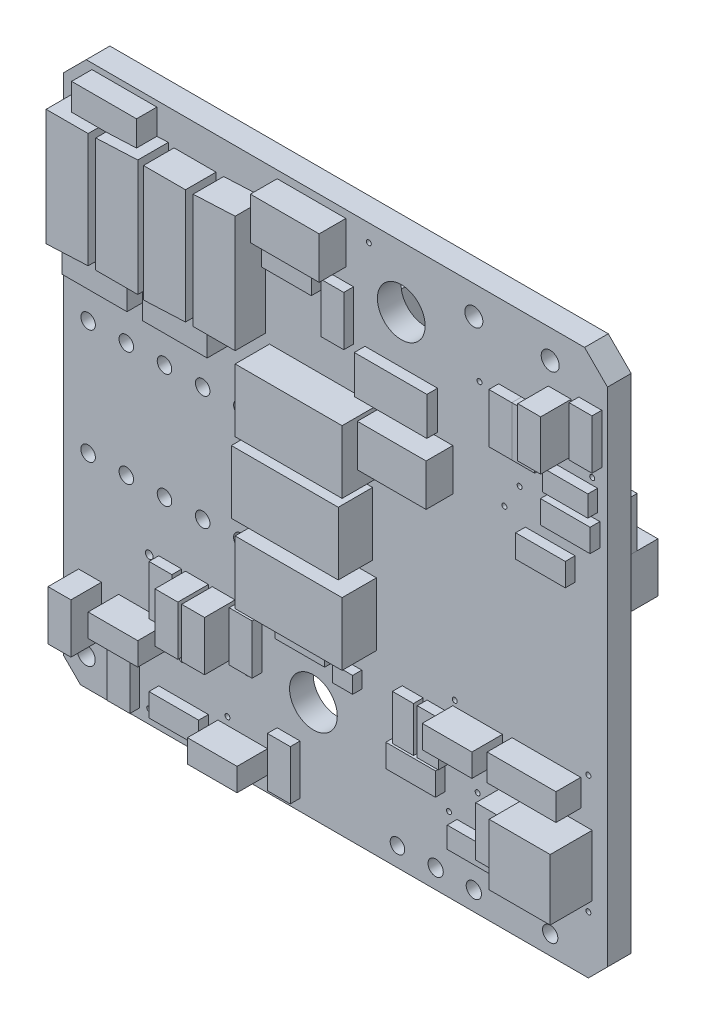
SolidWorks part; units mm, degrees
ref_plane "Front Plane" through (0, 0, 0) normal (0, 0, 1) x (1, 0, 0)
ref_plane "Top Plane" through (0, 0, 0) normal (0, 1, 0) x (1, 0, 0)
ref_plane "Right Plane" through (0, 0, 0) normal (1, 0, 0) x (0, 0, -1)
sketch "Sketch1" plane through (0, 0, 0) normal (0, 0, 1) x (1, 0, 0)
  line L0 (26.67, 71.501) -> (25.146, 69.977)
  line L1 (25.146, 69.977) -> (25.146, 36.449)
  line L2 (25.146, 36.449) -> (26.289, 35.306)
  line L3 (26.289, 35.306) -> (60.071, 35.306)
  line L4 (60.071, 35.306) -> (61.341, 36.576)
  line L5 (61.341, 36.576) -> (61.341, 69.977)
  line L6 (61.341, 69.977) -> (59.817, 71.501)
  line L7 (59.817, 71.501) -> (26.67, 71.501)
extrude "BOARD" add sketch "Sketch1" along normal blind 1.5748 separate body
sketch "Sketch2" plane through (0, 0, 0) normal (0, 0, 1) x (1, 0, 0)
  circle A0 centre (41.783, 42.037) radius 1.5875
  circle A1 centre (47.625, 67.437) radius 1.5875
extrude "NON-PLATED HOLES" cut sketch "Sketch2" along normal through all
sketch "Sketch3" plane through (0, 0, 0) normal (0, 0, 1) x (1, 0, 0)
  circle A0 centre (26.67, 69.723) radius 0.1651
  circle A1 centre (37.338, 41.529) radius 0.1651
  circle A2 centre (33.02, 40.132) radius 0.1651
  circle A3 centre (52.705, 44.323) radius 0.1651
  circle A4 centre (52.705, 42.291) radius 0.1651
  circle A5 centre (50.8, 40.259) radius 0.1651
  circle A6 centre (51.181, 46.863) radius 0.1651
  circle A7 centre (47.371, 57.531) radius 0.1651
  circle A8 centre (52.832, 66.04) radius 0.1651
  circle A9 centre (57.531, 36.576) radius 0.508
  circle A10 centre (60.071, 39.116) radius 0.1651
  circle A11 centre (60.071, 46.99) radius 0.1651
  circle A12 centre (54.483, 59.69) radius 0.1651
  circle A13 centre (60.325, 64.262) radius 0.1651
  circle A14 centre (26.67, 37.211) radius 0.6
  circle A15 centre (36.068, 38.354) radius 0.1651
  circle A16 centre (55.499, 61.341) radius 0.1651
  circle A17 centre (56.134, 38.1) radius 0.1651
  circle A18 centre (57.531, 69.596) radius 0.6
  circle A19 centre (30.861, 36.195) radius 0.1651
  circle A20 centre (52.451, 36.576) radius 0.508
  circle A21 centre (49.911, 36.576) radius 0.508
  circle A22 centre (47.371, 36.576) radius 0.4826
  circle A23 centre (38.1, 51.689) radius 0.1651
  circle A24 centre (45.466, 70.358) radius 0.1651
  circle A25 centre (30.861, 45.085) radius 0.254
  circle A26 centre (52.451, 69.596) radius 0.6
  circle A27 centre (26.797, 48.895) radius 0.4826
  circle A28 centre (31.877, 48.895) radius 0.4826
  circle A29 centre (34.417, 48.895) radius 0.4826
  circle A30 centre (26.797, 56.515) radius 0.4826
  circle A31 centre (31.877, 56.515) radius 0.4826
  circle A32 centre (34.417, 56.515) radius 0.4826
  circle A33 centre (29.337, 48.895) radius 0.4826
  circle A34 centre (36.957, 48.895) radius 0.4826
  circle A35 centre (29.337, 56.515) radius 0.4826
  circle A36 centre (36.957, 56.515) radius 0.4826
extrude "PLATED HOLES" cut sketch "Sketch3" along normal through all
ref_plane "Plane1" through (0, 0, 1.5748) normal (0, 0, 1) x (1, 0, 0)
sketch "Sketch4" plane through (0, 0, 1.5748) normal (0, 0, 1) x (1, 0, 0)
  line L0 (27.686, 38.608) -> (27.686, 41.91)
  line L1 (27.686, 41.91) -> (26.162, 41.91)
  line L2 (26.162, 41.91) -> (26.162, 38.608)
  line L3 (26.162, 38.608) -> (27.686, 38.608)
extrude "0805C-1" add sketch "Sketch4" along normal blind 2.032 separate body
sketch "Sketch5" plane through (0, 0, 1.5748) normal (0, 0, 1) x (1, 0, 0)
  line L0 (44.45, 64.008) -> (44.45, 67.31)
  line L1 (44.45, 67.31) -> (42.926, 67.31)
  line L2 (42.926, 67.31) -> (42.926, 64.008)
  line L3 (42.926, 64.008) -> (44.45, 64.008)
extrude "0805R-1" add sketch "Sketch5" along normal blind 0.6502 separate body
sketch "Sketch6" plane through (0, 0, 1.5748) normal (0, 0, 1) x (1, 0, 0)
  line L0 (42.291, 67.564) -> (38.989, 67.564)
  line L1 (38.989, 67.564) -> (38.989, 66.04)
  line L2 (38.989, 66.04) -> (42.291, 66.04)
  line L3 (42.291, 66.04) -> (42.291, 67.564)
extrude "0805R-2" add sketch "Sketch6" along normal blind 0.6502 separate body
sketch "Sketch7" plane through (0, 0, 0) normal (0, 0, 1) x (1, 0, 0)
  line L0 (47.752, 52.197) -> (51.054, 52.197)
  line L1 (51.054, 52.197) -> (51.054, 50.673)
  line L2 (51.054, 50.673) -> (47.752, 50.673)
  line L3 (47.752, 50.673) -> (47.752, 52.197)
extrude "0805C-2" add sketch "Sketch7" against normal blind 2.032 separate body
sketch "SOT23-5-1 [0]" plane through (0, 0, 0) normal (0, 0, 1) x (1, 0, 0)
  line L0 (50.8508, 48.9458) -> (50.8508, 47.5488)
  line L1 (50.8508, 47.5488) -> (47.9552, 47.5488)
  line L2 (47.9552, 47.5488) -> (47.9552, 48.9458)
  line L3 (47.9552, 48.9458) -> (50.8508, 48.9458)
sketch "Sketch9" plane through (0, 0, 0) normal (0, 0, 1) x (1, 0, 0)
  line L0 (50.2539, 62.3158) -> (50.2539, 63.6682)
  line L1 (50.2539, 63.6682) -> (51.3461, 63.6682)
  line L2 (51.3461, 63.6682) -> (51.3461, 62.3158)
  line L3 (51.3461, 62.3158) -> (50.2539, 62.3158)
extrude "SOD523-1" add sketch "Sketch9" against normal blind 0.6096 separate body
sketch "Sketch10" plane through (0, 0, 1.5748) normal (0, 0, 1) x (1, 0, 0)
  line L0 (60.325, 39.878) -> (60.325, 43.942)
  line L1 (60.325, 43.942) -> (56.261, 43.942)
  line L2 (56.261, 43.942) -> (56.261, 39.878)
  line L3 (56.261, 39.878) -> (60.325, 39.878)
extrude "L3838-1" add sketch "Sketch10" along normal blind 2.794 separate body
sketch "Sketch11" plane through (0, 0, 1.5748) normal (0, 0, 1) x (1, 0, 0)
  line L0 (55.88, 57.658) -> (59.182, 57.658)
  line L1 (59.182, 57.658) -> (59.182, 59.182)
  line L2 (59.182, 59.182) -> (55.88, 59.182)
  line L3 (55.88, 59.182) -> (55.88, 57.658)
extrude "0805R-3" add sketch "Sketch11" along normal blind 0.6502 separate body
sketch "Sketch12" plane through (0, 0, 0) normal (0, 0, 1) x (1, 0, 0)
  line L0 (56.007, 67.564) -> (59.309, 67.564)
  line L1 (59.309, 67.564) -> (59.309, 66.04)
  line L2 (59.309, 66.04) -> (56.007, 66.04)
  line L3 (56.007, 66.04) -> (56.007, 67.564)
extrude "0805C-3" add sketch "Sketch12" against normal blind 2.032 separate body
sketch "Sketch13" plane through (0, 0, 1.5748) normal (0, 0, 1) x (1, 0, 0)
  line L0 (57.682, 63.819) -> (57.682, 62.419)
  line L1 (57.682, 62.419) -> (60.682, 62.419)
  line L2 (60.682, 62.419) -> (60.682, 63.819)
  line L3 (60.682, 63.819) -> (57.682, 63.819)
extrude "RC0603-1" add sketch "Sketch13" along normal blind 0.6502 separate body
sketch "Sketch14" plane through (0, 0, 1.5748) normal (0, 0, 1) x (1, 0, 0)
  line L0 (55.626, 66.548) -> (55.626, 63.246)
  line L1 (55.626, 63.246) -> (57.15, 63.246)
  line L2 (57.15, 63.246) -> (57.15, 66.548)
  line L3 (57.15, 66.548) -> (55.626, 66.548)
extrude "0805R-4" add sketch "Sketch14" along normal blind 0.6502 separate body
sketch "Sketch15" plane through (0, 0, 1.5748) normal (0, 0, 1) x (1, 0, 0)
  line L0 (34.798, 37.846) -> (31.496, 37.846)
  line L1 (31.496, 37.846) -> (31.496, 36.322)
  line L2 (31.496, 36.322) -> (34.798, 36.322)
  line L3 (34.798, 36.322) -> (34.798, 37.846)
extrude "0805R-5" add sketch "Sketch15" along normal blind 0.6502 separate body
sketch "Sketch16" plane through (0, 0, 1.5748) normal (0, 0, 1) x (1, 0, 0)
  line L0 (34.798, 42.037) -> (34.798, 45.339)
  line L1 (34.798, 45.339) -> (33.274, 45.339)
  line L2 (33.274, 45.339) -> (33.274, 42.037)
  line L3 (33.274, 42.037) -> (34.798, 42.037)
extrude "0805C-4" add sketch "Sketch16" along normal blind 2.032 separate body
sketch "SOT23-1" plane through (0, 0, 1.5748) normal (0, 0, 1) x (1, 0, 0)
  line L0 (34.671, 39.243) -> (35.687, 39.243)
  line L1 (35.687, 39.243) -> (35.687, 40.767)
  line L2 (35.687, 40.767) -> (35.687, 39.243)
  line L3 (35.687, 39.243) -> (34.671, 39.243)
sketch "Sketch18" plane through (0, 0, 1.5748) normal (0, 0, 1) x (1, 0, 0)
  line L0 (33.02, 42.037) -> (33.02, 45.339)
  line L1 (33.02, 45.339) -> (31.496, 45.339)
  line L2 (31.496, 45.339) -> (31.496, 42.037)
  line L3 (31.496, 42.037) -> (33.02, 42.037)
extrude "0805R-6" add sketch "Sketch18" along normal blind 0.6502 separate body
sketch "Sketch19" plane through (0, 0, 1.5748) normal (0, 0, 1) x (1, 0, 0)
  line L0 (36.576, 42.037) -> (36.576, 45.339)
  line L1 (36.576, 45.339) -> (35.052, 45.339)
  line L2 (35.052, 45.339) -> (35.052, 42.037)
  line L3 (35.052, 42.037) -> (36.576, 42.037)
extrude "0805C-5" add sketch "Sketch19" along normal blind 2.032 separate body
sketch "Sketch20" plane through (0, 0, 1.5748) normal (0, 0, 1) x (1, 0, 0)
  line L0 (39.37, 39.37) -> (39.37, 36.068)
  line L1 (39.37, 36.068) -> (40.894, 36.068)
  line L2 (40.894, 36.068) -> (40.894, 39.37)
  line L3 (40.894, 39.37) -> (39.37, 39.37)
extrude "0805R-7" add sketch "Sketch20" along normal blind 0.6502 separate body
sketch "Sketch21" plane through (0, 0, 1.5748) normal (0, 0, 1) x (1, 0, 0)
  line L0 (39.878, 45.085) -> (43.18, 45.085)
  line L1 (43.18, 45.085) -> (43.18, 46.609)
  line L2 (43.18, 46.609) -> (39.878, 46.609)
  line L3 (39.878, 46.609) -> (39.878, 45.085)
extrude "0805R-8" add sketch "Sketch21" along normal blind 0.6502 separate body
sketch "Sketch22" plane through (0, 0, 0) normal (0, 0, 1) x (1, 0, 0)
  line L0 (49.784, 58.674) -> (49.784, 61.976)
  line L1 (49.784, 61.976) -> (51.308, 61.976)
  line L2 (51.308, 61.976) -> (51.308, 58.674)
  line L3 (51.308, 58.674) -> (49.784, 58.674)
extrude "0805C-6" add sketch "Sketch22" against normal blind 2.032 separate body
sketch "Sketch23" plane through (0, 0, 1.5748) normal (0, 0, 1) x (1, 0, 0)
  line L0 (49.338, 42.95) -> (50.738, 42.95)
  line L1 (50.738, 42.95) -> (50.738, 45.95)
  line L2 (50.738, 45.95) -> (49.338, 45.95)
  line L3 (49.338, 45.95) -> (49.338, 42.95)
extrude "RC0603-2" add sketch "Sketch23" along normal blind 0.6502 separate body
sketch "Sketch24" plane through (0, 0, 1.5748) normal (0, 0, 1) x (1, 0, 0)
  line L0 (47.687, 42.95) -> (49.087, 42.95)
  line L1 (49.087, 42.95) -> (49.087, 45.95)
  line L2 (49.087, 45.95) -> (47.687, 45.95)
  line L3 (47.687, 45.95) -> (47.687, 42.95)
extrude "RC0603-3" add sketch "Sketch24" along normal blind 0.6502 separate body
sketch "Sketch25" plane through (0, 0, 0) normal (0, 0, 1) x (1, 0, 0)
  line L0 (47.879, 46.101) -> (51.181, 46.101)
  line L1 (51.181, 46.101) -> (51.181, 44.577)
  line L2 (51.181, 44.577) -> (47.879, 44.577)
  line L3 (47.879, 44.577) -> (47.879, 46.101)
extrude "0805C-7" add sketch "Sketch25" against normal blind 2.032 separate body
sketch "Sketch26" plane through (0, 0, 0) normal (0, 0, 1) x (1, 0, 0)
  line L0 (49.911, 54.356) -> (49.911, 57.658)
  line L1 (49.911, 57.658) -> (51.435, 57.658)
  line L2 (51.435, 57.658) -> (51.435, 54.356)
  line L3 (51.435, 54.356) -> (49.911, 54.356)
extrude "0805C-8" add sketch "Sketch26" against normal blind 2.032 separate body
sketch "Sketch27" plane through (0, 0, 1.5748) normal (0, 0, 1) x (1, 0, 0)
  line L0 (51.054, 58.674) -> (51.054, 61.468)
  line L1 (51.054, 61.468) -> (46.482, 61.468)
  line L2 (46.482, 61.468) -> (46.482, 58.674)
  line L3 (46.482, 58.674) -> (51.054, 58.674)
extrude "1210HV-1" add sketch "Sketch27" along normal blind 1.778 separate body
sketch "Sketch28" plane through (0, 0, 0) normal (0, 0, 1) x (1, 0, 0)
  line L0 (49.911, 57.658) -> (49.911, 54.356)
  line L1 (49.911, 54.356) -> (48.387, 54.356)
  line L2 (48.387, 54.356) -> (48.387, 57.658)
  line L3 (48.387, 57.658) -> (49.911, 57.658)
extrude "0805R-9" add sketch "Sketch28" against normal blind 0.6502 separate body
sketch "Sketch29" plane through (0, 0, 1.5748) normal (0, 0, 1) x (1, 0, 0)
  line L0 (54.61, 43.688) -> (54.61, 40.386)
  line L1 (54.61, 40.386) -> (56.134, 40.386)
  line L2 (56.134, 40.386) -> (56.134, 43.688)
  line L3 (56.134, 43.688) -> (54.61, 43.688)
extrude "0805C-9" add sketch "Sketch29" along normal blind 2.032 separate body
sketch "Sketch30" plane through (0, 0, 1.5748) normal (0, 0, 1) x (1, 0, 0)
  line L0 (59.563, 44.831) -> (59.563, 46.609)
  line L1 (59.563, 46.609) -> (54.991, 46.609)
  line L2 (54.991, 46.609) -> (54.991, 44.831)
  line L3 (54.991, 44.831) -> (59.563, 44.831)
extrude "DIODE_SMF-1" add sketch "Sketch30" along normal blind 1.651 separate body
sketch "Sketch31" plane through (0, 0, 1.5748) normal (0, 0, 1) x (1, 0, 0)
  line L0 (26.035, 61.595) -> (28.829, 61.722)
  line L1 (28.829, 61.722) -> (28.829, 69.342)
  line L2 (28.829, 69.342) -> (26.035, 69.342)
  line L3 (26.035, 69.342) -> (26.035, 61.722)
  line L4 (26.035, 61.722) -> (26.035, 61.595)
extrude "MICROSEMI_A-1" add sketch "Sketch31" along normal blind 2.032 separate body
sketch "Sketch32" plane through (0, 0, 1.5748) normal (0, 0, 1) x (1, 0, 0)
  line L0 (32.512, 61.595) -> (35.306, 61.722)
  line L1 (35.306, 61.722) -> (35.306, 69.342)
  line L2 (35.306, 69.342) -> (32.512, 69.342)
  line L3 (32.512, 69.342) -> (32.512, 61.722)
  line L4 (32.512, 61.722) -> (32.512, 61.595)
extrude "MICROSEMI_A-2" add sketch "Sketch32" along normal blind 2.032 separate body
sketch "Sketch33" plane through (0, 0, 1.5748) normal (0, 0, 1) x (1, 0, 0)
  line L0 (57.404, 68.072) -> (57.404, 64.77)
  line L1 (57.404, 64.77) -> (58.928, 64.77)
  line L2 (58.928, 64.77) -> (58.928, 68.072)
  line L3 (58.928, 68.072) -> (57.404, 68.072)
extrude "0805C-10" add sketch "Sketch33" along normal blind 2.032 separate body
sketch "Sketch34" plane through (0, 0, 1.5748) normal (0, 0, 1) x (1, 0, 0)
  line L0 (32.131, 41.783) -> (28.829, 41.783)
  line L1 (28.829, 41.783) -> (28.829, 40.259)
  line L2 (28.829, 40.259) -> (32.131, 40.259)
  line L3 (32.131, 40.259) -> (32.131, 41.783)
extrude "0805C-11" add sketch "Sketch34" along normal blind 2.032 separate body
sketch "Sketch35" plane through (0, 0, 1.5748) normal (0, 0, 1) x (1, 0, 0)
  line L0 (27.051, 71.12) -> (27.051, 69.342)
  line L1 (27.051, 69.342) -> (31.369, 69.342)
  line L2 (31.369, 69.342) -> (31.369, 71.12)
  line L3 (31.369, 71.12) -> (27.051, 71.12)
extrude "1206C-1" add sketch "Sketch35" along normal blind 1.3513 separate body
sketch "CONN3_100-1 [0]" plane through (0, 0, 1.5748) normal (0, 0, 1) x (1, 0, 0)
  line L0 (46.101, 37.846) -> (46.101, 35.306)
  line L1 (46.101, 35.306) -> (53.721, 35.306)
  line L2 (53.721, 35.306) -> (53.721, 37.846)
  line L3 (53.721, 37.846) -> (46.101, 37.846)
sketch "Sketch37" plane through (0, 0, 1.5748) normal (0, 0, 1) x (1, 0, 0)
  line L0 (38.354, 42.037) -> (38.354, 45.339)
  line L1 (38.354, 45.339) -> (36.83, 45.339)
  line L2 (36.83, 45.339) -> (36.83, 42.037)
  line L3 (36.83, 42.037) -> (38.354, 42.037)
extrude "0805R-10" add sketch "Sketch37" along normal blind 0.6502 separate body
sketch "Sketch38" plane through (0, 0, 1.5748) normal (0, 0, 1) x (1, 0, 0)
  line L0 (50.546, 42.799) -> (47.244, 42.799)
  line L1 (47.244, 42.799) -> (47.244, 41.275)
  line L2 (47.244, 41.275) -> (50.546, 41.275)
  line L3 (50.546, 41.275) -> (50.546, 42.799)
extrude "0805R-11" add sketch "Sketch38" along normal blind 0.6502 separate body
sketch "Sketch39" plane through (0, 0, 1.5748) normal (0, 0, 1) x (1, 0, 0)
  line L0 (51.332, 40.07) -> (51.332, 38.67)
  line L1 (51.332, 38.67) -> (54.332, 38.67)
  line L2 (54.332, 38.67) -> (54.332, 40.07)
  line L3 (54.332, 40.07) -> (51.332, 40.07)
extrude "RC0603-4" add sketch "Sketch39" along normal blind 0.6502 separate body
sketch "SOT23-5-2 [0]" plane through (0, 0, 1.5748) normal (0, 0, 1) x (1, 0, 0)
  line L0 (54.1528, 41.3512) -> (54.1528, 42.7482)
  line L1 (54.1528, 42.7482) -> (51.2572, 42.7482)
  line L2 (51.2572, 42.7482) -> (51.2572, 41.3512)
  line L3 (51.2572, 41.3512) -> (54.1528, 41.3512)
sketch "Sketch41" plane through (0, 0, 1.5748) normal (0, 0, 1) x (1, 0, 0)
  line L0 (45.974, 47.117) -> (45.974, 51.308)
  line L1 (45.974, 51.308) -> (38.862, 51.308)
  line L2 (38.862, 51.308) -> (38.862, 47.117)
  line L3 (38.862, 47.117) -> (45.974, 47.117)
extrude "DIODESMB-1" add sketch "Sketch41" along normal blind 2.286 separate body
sketch "Sketch42" plane through (0, 0, 0) normal (0, 0, 1) x (1, 0, 0)
  line L0 (59.563, 56.007) -> (59.563, 59.309)
  line L1 (59.563, 59.309) -> (61.087, 59.309)
  line L2 (61.087, 59.309) -> (61.087, 56.007)
  line L3 (61.087, 56.007) -> (59.563, 56.007)
extrude "0805C-12" add sketch "Sketch42" against normal blind 2.032 separate body
sketch "Sketch43" plane through (0, 0, 1.5748) normal (0, 0, 1) x (1, 0, 0)
  line L0 (54.102, 66.548) -> (54.102, 63.246)
  line L1 (54.102, 63.246) -> (55.626, 63.246)
  line L2 (55.626, 63.246) -> (55.626, 66.548)
  line L3 (55.626, 66.548) -> (54.102, 66.548)
extrude "0805R-12" add sketch "Sketch43" along normal blind 0.6502 separate body
sketch "Sketch44" plane through (0, 0, 1.5748) normal (0, 0, 1) x (1, 0, 0)
  line L0 (50.038, 61.722) -> (50.038, 64.262)
  line L1 (50.038, 64.262) -> (45.212, 64.262)
  line L2 (45.212, 64.262) -> (45.212, 61.722)
  line L3 (45.212, 61.722) -> (50.038, 61.722)
extrude "1206RHV-1" add sketch "Sketch44" along normal blind 0.7112 separate body
sketch "Sketch45" plane through (0, 0, 1.5748) normal (0, 0, 1) x (1, 0, 0)
  line L0 (26.416, 61.468) -> (26.416, 59.69)
  line L1 (26.416, 59.69) -> (30.734, 59.69)
  line L2 (30.734, 59.69) -> (30.734, 61.468)
  line L3 (30.734, 61.468) -> (26.416, 61.468)
extrude "1206C-2" add sketch "Sketch45" along normal blind 1.3513 separate body
sketch "SOT23-2" plane through (0, 0, 1.5748) normal (0, 0, 1) x (1, 0, 0)
  line L0 (30.353, 44.323) -> (30.353, 45.339)
  line L1 (30.353, 45.339) -> (28.829, 45.339)
  line L2 (28.829, 45.339) -> (30.353, 45.339)
  line L3 (30.353, 45.339) -> (30.353, 44.323)
sketch "Sketch47" plane through (0, 0, 1.5748) normal (0, 0, 1) x (1, 0, 0)
  line L0 (28.702, 39.243) -> (28.702, 35.941)
  line L1 (28.702, 35.941) -> (30.226, 35.941)
  line L2 (30.226, 35.941) -> (30.226, 39.243)
  line L3 (30.226, 39.243) -> (28.702, 39.243)
extrude "0805R-13" add sketch "Sketch47" along normal blind 0.6502 separate body
sketch "Sketch48" plane through (0, 0, 0) normal (0, 0, 1) x (1, 0, 0)
  line L0 (61.087, 62.611) -> (61.087, 59.309)
  line L1 (61.087, 59.309) -> (59.563, 59.309)
  line L2 (59.563, 59.309) -> (59.563, 62.611)
  line L3 (59.563, 62.611) -> (61.087, 62.611)
extrude "0805R-14" add sketch "Sketch48" against normal blind 0.6502 separate body
sketch "SOT23-3" plane through (0, 0, 1.5748) normal (0, 0, 1) x (1, 0, 0)
  line L0 (37.973, 39.243) -> (38.989, 39.243)
  line L1 (38.989, 39.243) -> (38.989, 40.767)
  line L2 (38.989, 40.767) -> (38.989, 39.243)
  line L3 (38.989, 39.243) -> (37.973, 39.243)
sketch "Sketch50" plane through (0, 0, 1.5748) normal (0, 0, 1) x (1, 0, 0)
  line L0 (54.356, 46.482) -> (51.054, 46.482)
  line L1 (51.054, 46.482) -> (51.054, 44.958)
  line L2 (51.054, 44.958) -> (54.356, 44.958)
  line L3 (54.356, 44.958) -> (54.356, 46.482)
extrude "0805C-13" add sketch "Sketch50" along normal blind 2.032 separate body
sketch "Sketch51" plane through (0, 0, 1.5748) normal (0, 0, 1) x (1, 0, 0)
  line L0 (57.531, 60.452) -> (60.833, 60.452)
  line L1 (60.833, 60.452) -> (60.833, 61.976)
  line L2 (60.833, 61.976) -> (57.531, 61.976)
  line L3 (57.531, 61.976) -> (57.531, 60.452)
extrude "0805R-15" add sketch "Sketch51" along normal blind 0.6502 separate body
sketch "SOT23-4" plane through (0, 0, 1.5748) normal (0, 0, 1) x (1, 0, 0)
  line L0 (56.007, 60.452) -> (57.023, 60.452)
  line L1 (57.023, 60.452) -> (57.023, 61.976)
  line L2 (57.023, 61.976) -> (57.023, 60.452)
  line L3 (57.023, 60.452) -> (56.007, 60.452)
sketch "Sketch53" plane through (0, 0, 1.5748) normal (0, 0, 1) x (1, 0, 0)
  line L0 (35.433, 36.322) -> (38.735, 36.322)
  line L1 (38.735, 36.322) -> (38.735, 37.846)
  line L2 (38.735, 37.846) -> (35.433, 37.846)
  line L3 (35.433, 37.846) -> (35.433, 36.322)
extrude "0805C-14" add sketch "Sketch53" along normal blind 2.032 separate body
sketch "Sketch54" plane through (0, 0, 1.5748) normal (0, 0, 1) x (1, 0, 0)
  line L0 (44.9992, 45.5041) -> (43.6468, 45.5041)
  line L1 (43.6468, 45.5041) -> (43.6468, 44.4119)
  line L2 (43.6468, 44.4119) -> (44.9992, 44.4119)
  line L3 (44.9992, 44.4119) -> (44.9992, 45.5041)
extrude "SOD523-2" add sketch "Sketch54" along normal blind 0.6096 separate body
sketch "Sketch55" plane through (0, 0, 1.5748) normal (0, 0, 1) x (1, 0, 0)
  line L0 (38.608, 56.388) -> (38.608, 52.197)
  line L1 (38.608, 52.197) -> (45.72, 52.197)
  line L2 (45.72, 52.197) -> (45.72, 56.388)
  line L3 (45.72, 56.388) -> (38.608, 56.388)
extrude "DIODESMB-2" add sketch "Sketch55" along normal blind 2.286 separate body
sketch "Sketch56" plane through (0, 0, 1.5748) normal (0, 0, 1) x (1, 0, 0)
  line L0 (45.974, 57.023) -> (45.974, 61.214)
  line L1 (45.974, 61.214) -> (38.862, 61.214)
  line L2 (38.862, 61.214) -> (38.862, 57.023)
  line L3 (38.862, 57.023) -> (45.974, 57.023)
extrude "DIODESMB-3" add sketch "Sketch56" along normal blind 2.286 separate body
sketch "Sketch57" plane through (0, 0, 1.5748) normal (0, 0, 1) x (1, 0, 0)
  line L0 (60.96, 65.151) -> (60.96, 68.453)
  line L1 (60.96, 68.453) -> (59.436, 68.453)
  line L2 (59.436, 68.453) -> (59.436, 65.151)
  line L3 (59.436, 65.151) -> (60.96, 65.151)
extrude "0805R-16" add sketch "Sketch57" along normal blind 0.6502 separate body
sketch "Sketch58" plane through (0, 0, 1.5748) normal (0, 0, 1) x (1, 0, 0)
  line L0 (43.942, 68.199) -> (43.942, 70.993)
  line L1 (43.942, 70.993) -> (39.37, 70.993)
  line L2 (39.37, 70.993) -> (39.37, 68.199)
  line L3 (39.37, 68.199) -> (43.942, 68.199)
extrude "1210HV-2" add sketch "Sketch58" along normal blind 1.778 separate body
sketch "Sketch59" plane through (0, 0, 1.5748) normal (0, 0, 1) x (1, 0, 0)
  line L0 (32.131, 69.469) -> (29.337, 69.342)
  line L1 (29.337, 69.342) -> (29.337, 61.722)
  line L2 (29.337, 61.722) -> (32.131, 61.722)
  line L3 (32.131, 61.722) -> (32.131, 69.342)
  line L4 (32.131, 69.342) -> (32.131, 69.469)
extrude "MICROSEMI_A-3" add sketch "Sketch59" along normal blind 2.032 separate body
sketch "Sketch60" plane through (0, 0, 0) normal (0, 0, 1) x (1, 0, 0)
  line L0 (56.896, 55.372) -> (53.848, 55.372)
  line L1 (53.848, 55.372) -> (53.848, 65.913)
  line L2 (53.848, 65.913) -> (56.896, 65.913)
  line L3 (56.896, 65.913) -> (56.896, 55.372)
extrude "SO16-1" add sketch "Sketch60" against normal blind 2.6518 separate body
sketch "Sketch61" plane through (0, 0, 1.5748) normal (0, 0, 1) x (1, 0, 0)
  line L0 (38.608, 69.469) -> (35.814, 69.342)
  line L1 (35.814, 69.342) -> (35.814, 61.722)
  line L2 (35.814, 61.722) -> (38.608, 61.722)
  line L3 (38.608, 61.722) -> (38.608, 69.342)
  line L4 (38.608, 69.342) -> (38.608, 69.469)
extrude "MICROSEMI_A-4" add sketch "Sketch61" along normal blind 2.032 separate body
sketch "Sketch62" plane through (0, 0, 1.5748) normal (0, 0, 1) x (1, 0, 0)
  line L0 (31.75, 61.468) -> (31.75, 59.69)
  line L1 (31.75, 59.69) -> (36.068, 59.69)
  line L2 (36.068, 59.69) -> (36.068, 61.468)
  line L3 (36.068, 61.468) -> (31.75, 61.468)
extrude "1206C-3" add sketch "Sketch62" along normal blind 1.3513 separate body
sketch "Sketch63" plane through (0, 0, 0) normal (0, 0, 1) x (1, 0, 0)
  line L0 (38.227, 59.3725) -> (38.227, 46.0375)
  line L1 (38.227, 46.0375) -> (25.527, 46.0375)
  line L2 (25.527, 46.0375) -> (25.527, 59.3725)
  line L3 (25.527, 59.3725) -> (38.227, 59.3725)
extrude "DIP10-1" add sketch "Sketch63" against normal blind 9.525 separate body
